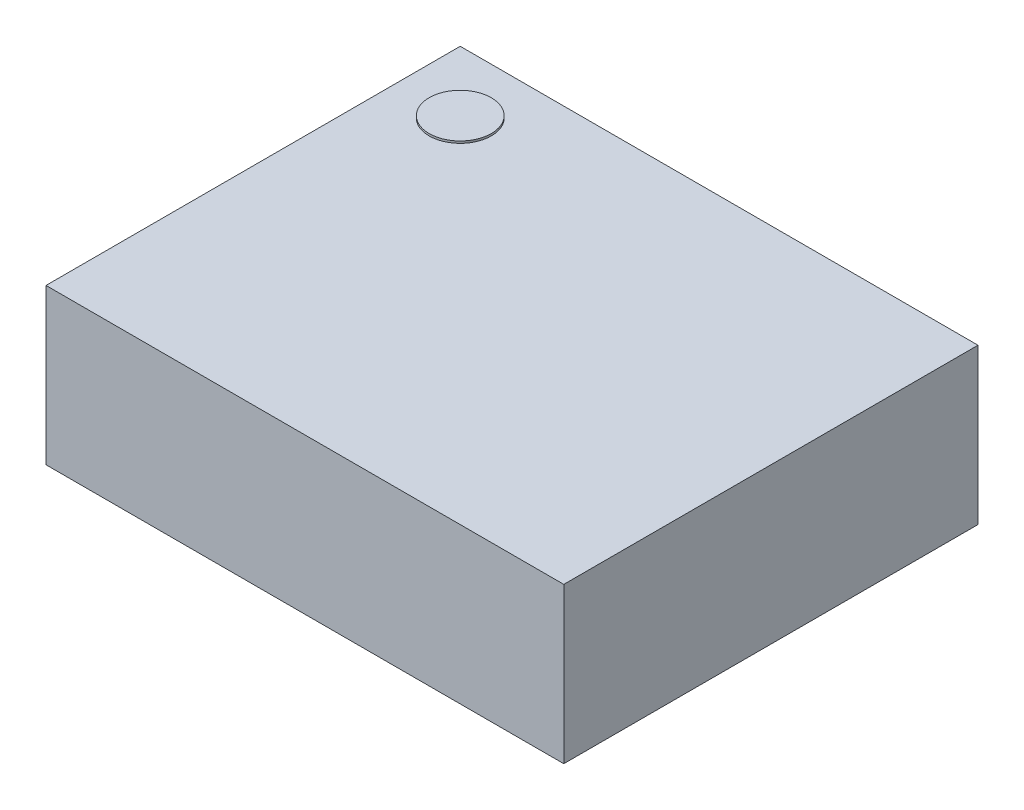
SolidWorks part; units mm, degrees
ref_plane "Front Plane" through (0, 0, 0) normal (0, 0, 1) x (1, 0, 0)
ref_plane "Top Plane" through (0, 0, 0) normal (0, 1, 0) x (1, 0, 0)
ref_plane "Right Plane" through (0, 0, 0) normal (1, 0, 0) x (0, 0, -1)
sketch "Sketch1" plane through (0, 0, 0) normal (0, 1, 0) x (1, 0, 0)
  line L1 (-18.4516, 10.6516) -> (-15.9516, 10.6516)
  line L2 (-18.4516, 10.6516) -> (-18.4516, 8.6516)
  line L3 (-18.4516, 8.6516) -> (-15.9516, 8.6516)
  line L4 (-15.9516, 10.6516) -> (-15.9516, 8.6516)
  dimension "D1" = 2.5
  dimension "D2" = 2
extrude "Boss-Extrude1" add sketch "Sketch1" along normal blind 0.75
sketch "Sketch2" plane through (0, 0.75, 0) normal (0, 1, 0) x (1, 0, 0)
  line L0 (-18.4516, 10.6516) -> (-18.4516, 8.6516) construction
  line L1 (-15.9516, 10.6516) -> (-18.4516, 10.6516) construction
  circle A0 centre (-18.1516, 10.3516) radius 0.15
  dimension "D3" = 0.3
  dimension "D1" = 0.3
  dimension "D2" = 0.3
extrude "Boss-Extrude2" add sketch "Sketch2" along normal blind 0.01
